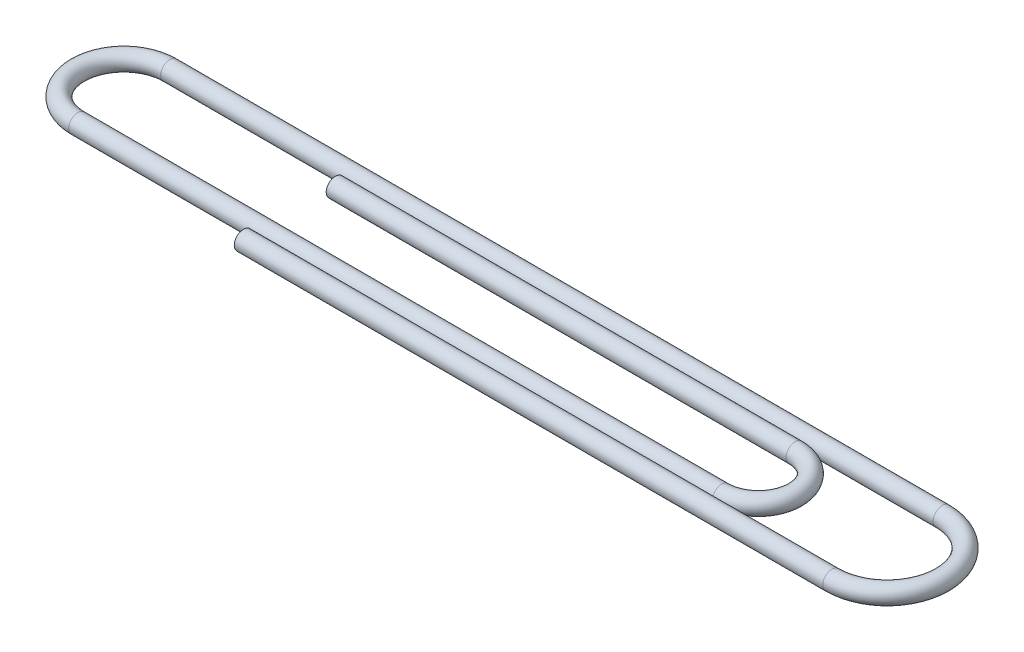
SolidWorks part; units mm, degrees
ref_plane "Front Plane" through (0, 0, 0) normal (0, 0, 1) x (1, 0, 0)
ref_plane "Top Plane" through (0, 0, 0) normal (0, 1, 0) x (1, 0, 0)
ref_plane "Right Plane" through (0, 0, 0) normal (1, 0, 0) x (0, 0, -1)
sketch "Sketch2" plane through (0, 0, 0) normal (0, 1, 0) x (1, 0, 0)
  line L0 (0, 0) -> (32, 0)
  line L1 (32, 6) -> (-10, 6)
  line L2 (-10, 1) -> (25, 1)
  line L3 (25, 5) -> (0, 5)
  arc A0 (32, 6) -> (32, 0) centre (32, 3) cw
  arc A1 (25, 5) -> (25, 1) centre (25, 3) cw
  arc A2 (-10, 6) -> (-10, 1) centre (-10, 3.5) ccw
  dimension "D6" = 2
  dimension "D5" = 3
  dimension "D1" = 42
  dimension "D2" = 25
  dimension "D3" = 35
  dimension "D4" = 32
sweep "Sweep1" add path "Sketch2" circular profile diameter 0.9999 parameters "D3"=0.9999
